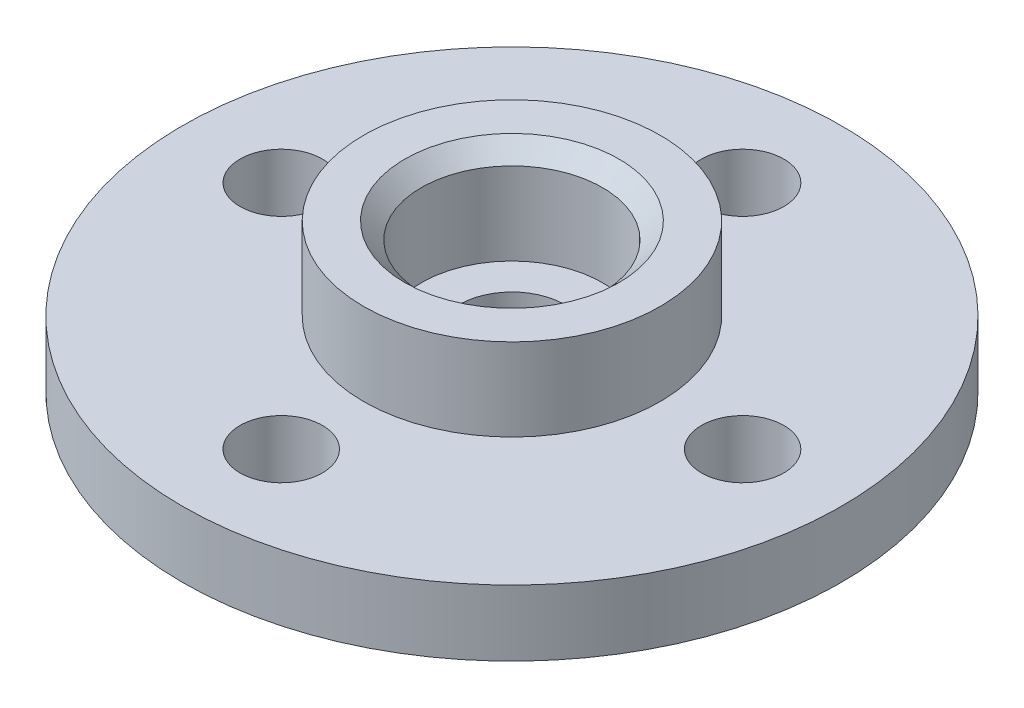
SolidWorks part; units mm, degrees
material "6061-T6 (SS)"
ref_plane "前视基准面" through (0, 0, 0) normal (0, 0, 1) x (1, 0, 0)
ref_plane "上视基准面" through (0, 0, 0) normal (0, 1, 0) x (1, 0, 0)
ref_plane "右视基准面" through (0, 0, 0) normal (1, 0, 0) x (0, 0, -1)
sketch "草图1" plane through (0, 0, 0) normal (0, 1, 0) x (1, 0, 0)
  circle A0 centre (0, 0) radius 10
  dimension "D1" = 20
extrude "凸台-拉伸1" add sketch "草图1" along normal blind 2
sketch "草图2" plane through (0, 2, 0) normal (0, 1, 0) x (1, 0, 0)
  circle A0 centre (0, 0) radius 4.5
  dimension "D1" = 9
extrude "凸台-拉伸2" add sketch "草图2" along normal blind 2.5
sketch "草图3" plane through (0, 2, 0) normal (0, 1, 0) x (1, 0, 0)
  circle A0 centre (0, 0) radius 7 construction
  point P3 (0, 7)
  point P4 (0, -7)
  point P5 (-7, 0)
  point P6 (7, 0)
  point P7 (-15.8085, 1.3028)
  dimension "D1" = 14
sketch "草图4" plane through (0, 2, 0) normal (0, 1, 0) x (1, 0, 0)
  circle A0 centre (0, 7) radius 1.25
  circle A1 centre (7, 0) radius 1.25
  circle A2 centre (0, -7) radius 1.25
  circle A3 centre (-7, 0) radius 1.25
  circle A4 centre (0, 0) radius 7 construction
  dimension "D1" = 2.5
  dimension "D2" = 4
extrude "切除-拉伸1" cut sketch "草图4" against normal blind 2.5
cosmetic thread "装饰螺纹线1" parameters "D2"=3
cosmetic thread "装饰螺纹线2" parameters "D2"=3
cosmetic thread "装饰螺纹线3" parameters "D2"=3
cosmetic thread "装饰螺纹线4" parameters "D2"=3
sketch "草图5" plane through (0, 4.5, 0) normal (0, 1, 0) x (1, 0, 0)
  circle A0 centre (0, 0) radius 2.75
  dimension "D1" = 5.5
extrude "切除-拉伸2" cut sketch "草图5" against normal blind 3
sketch "草图6" plane through (0, 1.5, 0) normal (0, 1, 0) x (1, 0, 0)
  circle A0 centre (0, 0) radius 1.6
  dimension "D1" = 3.2
extrude "切除-拉伸3" cut sketch "草图6" against normal blind 3
chamfer "倒角1" distance 0.5 angle 45 1 edges at (0, 4.5, 2.75)
